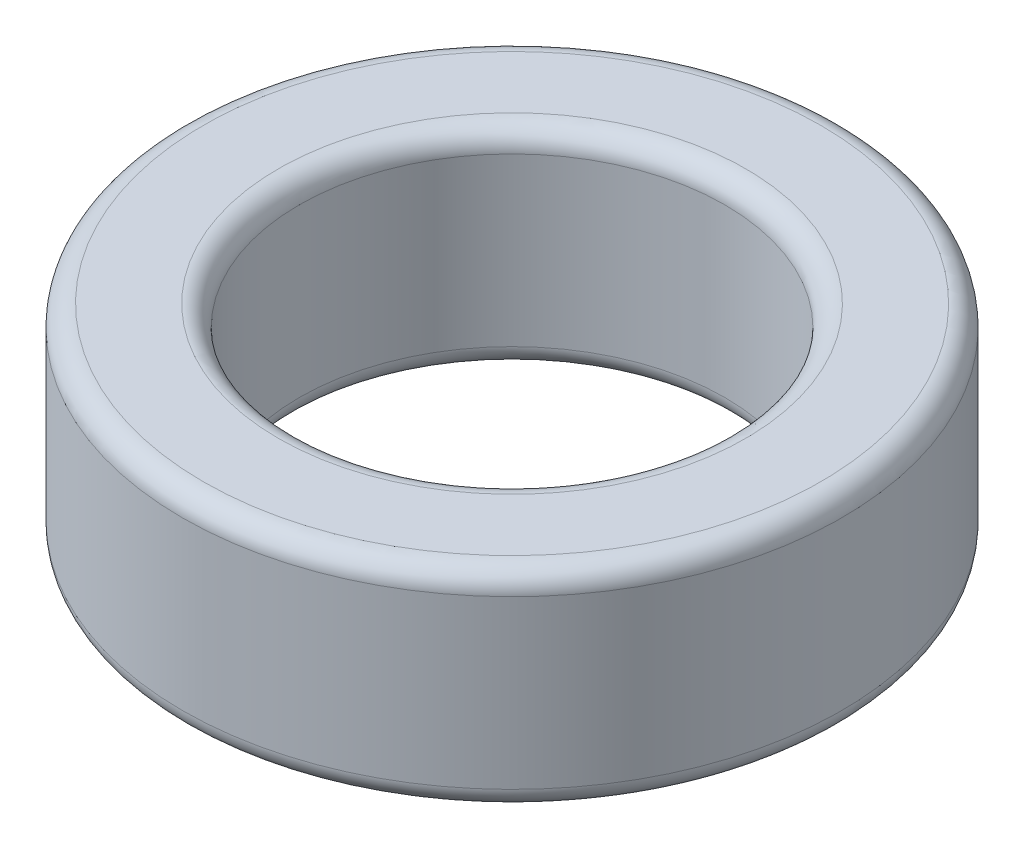
SolidWorks part; units mm, degrees
ref_plane "前基準面" through (0, 0, 0) normal (0, 0, 1) x (1, 0, 0)
ref_plane "上基準面" through (0, 0, 0) normal (0, 1, 0) x (1, 0, 0)
ref_plane "右基準面" through (0, 0, 0) normal (1, 0, 0) x (0, 0, -1)
sketch "草圖1" plane through (0, 0, 0) normal (0, 1, 0) x (1, 0, 0)
  circle A0 centre (0, 0) radius 7.9
  circle A1 centre (0, 0) radius 5.1
  dimension "D1" = 15.8
  dimension "D2" = 10.2
extrude "填料-伸長1" add sketch "草圖1" along normal blind 5
fillet "圓角1" radius 0.5 4 edges at (0, 0, 7.9) (0, 0, 5.1) (0, 5, 5.1) (0, 5, 7.9)
